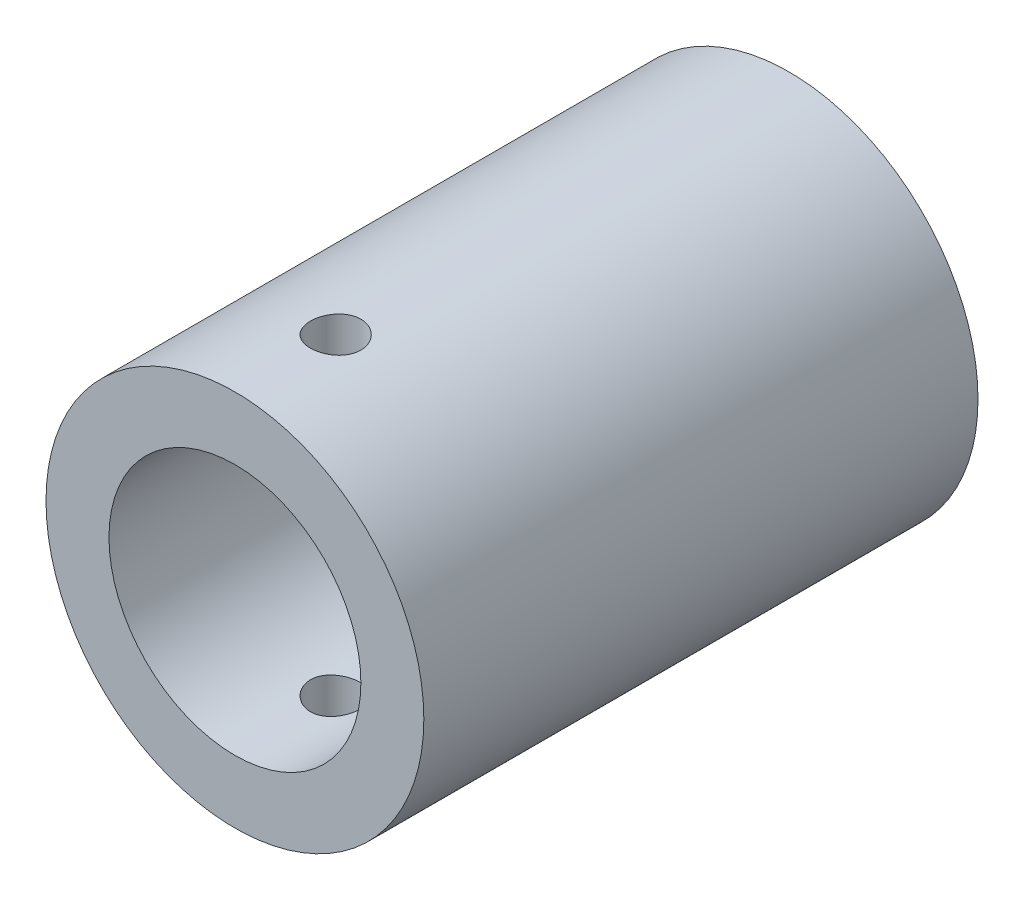
SolidWorks part; units mm, degrees
material "7075-T6 (SN)"
ref_plane "Ön Düzlem" through (0, 0, 0) normal (0, 0, 1) x (1, 0, 0)
ref_plane "Üst Düzlem" through (0, 0, 0) normal (0, 1, 0) x (1, 0, 0)
ref_plane "Sağ Düzlem" through (0, 0, 0) normal (1, 0, 0) x (0, 0, -1)
sketch "Çizim1" plane through (0, 0, 0) normal (0, 0, 1) x (1, 0, 0)
  circle A0 centre (0, 0) radius 15
  dimension "D1" = 30
extrude "Yükseklik-Ekstrüzyon1" add sketch "Çizim1" along normal blind 44
ref_plane "Düzlem1" through (15, 0, 0) normal (1, 0, 0) x (0, 0, -1)
sketch "Çizim2" plane through (15, 0, 0) normal (1, 0, 0) x (0, 0, -1)
  line L0 (-35, 0) -> (0, 0) construction
  circle A0 centre (-35, 0) radius 2.5
  dimension "D1" = 5
  dimension "D2" = 35
sketch "Çizim3" plane through (0, 0, 44) normal (0, 0, 1) x (1, 0, 0)
  circle A0 centre (0, 0) radius 10
extrude "Kes-Ekstrüzyon1" cut sketch "Çizim3" against normal blind 30
ref_plane "Düzlem2" through (0, 15, 0) normal (0, 1, 0) x (1, 0, 0)
sketch "Çizim4" plane through (0, 15, 0) normal (0, 1, 0) x (1, 0, 0)
  line L0 (0, -44) -> (0, -38) construction
  line L1 (-15, -44) -> (15, -44) construction
  circle A0 centre (0, -36) radius 2
  dimension "D1" = 4
  dimension "D2" = 6
extrude "Kes-Ekstrüzyon2" cut sketch "Çizim4" against normal blind 60
